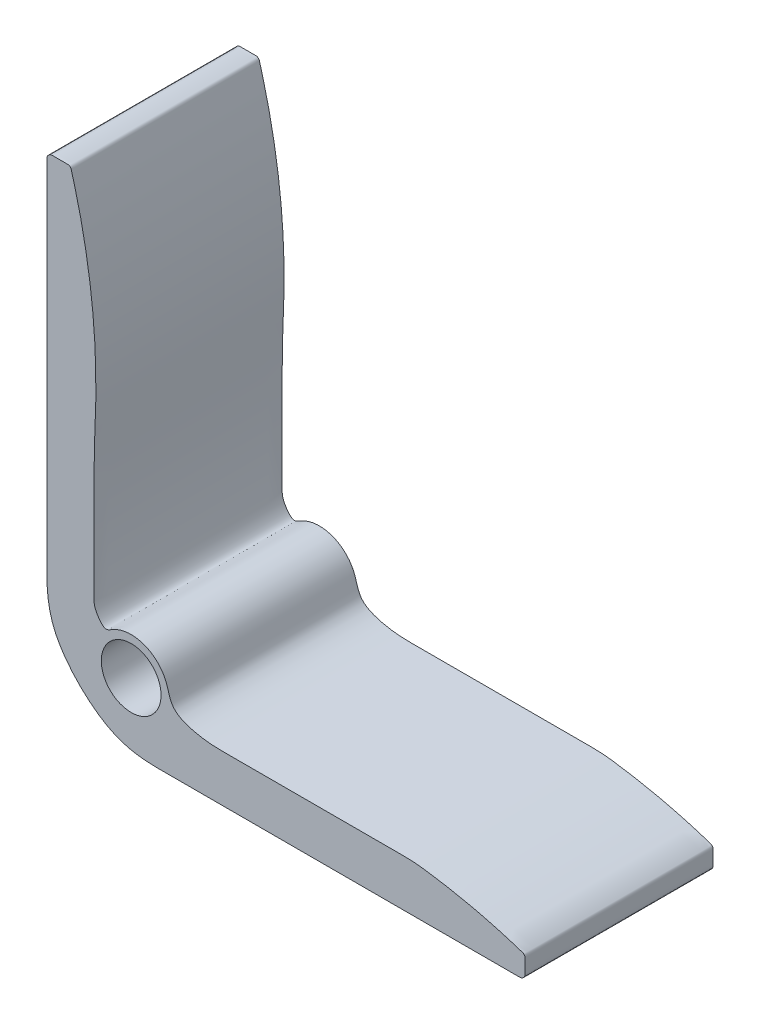
SolidWorks part; units mm, degrees
ref_plane "Alzado" through (0, 0, 0) normal (0, 0, 1) x (1, 0, 0)
ref_plane "Planta" through (0, 0, 0) normal (0, 1, 0) x (1, 0, 0)
ref_plane "Vista lateral" through (0, 0, 0) normal (1, 0, 0) x (0, 0, -1)
sketch "Croquis1" plane through (0, 0, 0) normal (0, 0, 1) x (1, 0, 0)
  line L0 (13.9712, -20.847) -> (-12.4747, -20.847) construction
  line L1 (25.847, -25.847) -> (-24.953, -25.847) construction
  line L2 (-19.953, -20.847) -> (-19.953, 19.953) construction
  line L3 (20.847, -20.847) -> (-19.953, -20.847) construction
  line L4 (-24.953, -25.847) -> (-24.953, 24.953) construction
  line L5 (25.847, -25.847) -> (0.447, -0.447) construction
  line L6 (-19.953, 19.953) -> (-24.953, 24.953) construction
  line L7 (-19.953, -18.3533) -> (-19.953, 0.7998) construction
  line L10 (25.847, 24.953) -> (-24.953, 24.953) construction
  line L11 (20.847, 19.953) -> (-19.953, 19.953) construction
  line L12 (0.447, -0.447) -> (-14.3951, -15.2892) construction
  line L13 (20.847, -20.847) -> (20.847, 19.953) construction
  line L14 (25.847, -25.847) -> (25.847, 24.953) construction
  line L15 (-21.6887, -22.5828) -> (-24.953, -25.847) construction
  line L16 (25.847, -25.847) -> (25.847, -23.4989) construction
  line L17 (-24.953, 24.953) -> (-22.453, 24.953) construction
  circle A0 centre (-15.9983, -18.9538) radius 3.175
  arc A1 (-12.4747, -20.847) -> (-19.953, -18.3533) centre (-15.9983, -18.9538) ccw construction
  arc A2 (25.847, -23.4989) -> (13.9712, -20.847) centre (7.3597, -78.3728) ccw construction
  arc A3 (-22.453, 24.953) -> (-19.953, 0.7998) centre (-87.0911, 6.0566) cw construction
  spline S0 degree 3 poles (-24.953, -13.147) (-24.953, -0.6554) (-24.953, 11.8363) (-24.953, 24.328) (-24.953, 24.4262) (-24.953, 24.6226) (-24.6226, 24.953) (-24.4262, 24.953) (-24.328, 24.953) (-23.9113, 24.953) (-23.4946, 24.953) (-23.078, 24.953) (-23.0431, 24.953) (-22.9735, 24.953) (-22.8691, 24.953) (-22.7994, 24.953) (-22.7646, 24.953) (-22.7091, 24.953) (-22.5982, 24.953) (-22.4119, 24.8126) (-22.3813, 24.706) (-22.3659, 24.6527) (-22.3563, 24.6193) (-22.3372, 24.5526) (-22.3087, 24.4523) (-22.2898, 24.3855) (-22.2803, 24.3521) (-20.674, 18.6619) (-19.8266, 12.8104) (-19.7527, 6.8984) (-19.7376, 5.6886) (-19.7726, 3.2683) (-19.953, -0.3589) (-19.953, -2.7786) (-19.953, -3.9885) (-19.953, -7.1807) (-19.953, -10.3729) (-19.953, -13.5651) (-19.953, -13.8672) (-19.953, -14.4714) (-18.8234, -16.0734) (-18.3437, -15.6996) (-18.086, -15.5419) (-15.8047, -14.146) (-13.2675, -14.992) (-12.2806, -17.4778) (-11.9834, -18.2263) (-11.8411, -19.9028) (-8.2792, -20.847) (-6.6686, -20.847) (-5.8632, -20.847) (-0.2675, -20.847) (5.3282, -20.847) (10.9239, -20.847) (11.1248, -20.847) (11.5266, -20.847) (12.1293, -20.847) (12.5311, -20.847) (12.732, -20.847) (13.0384, -20.847) (13.6511, -20.847) (14.5726, -20.912) (15.1793, -20.998) (15.4826, -21.0409) (15.6503, -21.0647) (15.9855, -21.1122) (16.4873, -21.1915) (16.8215, -21.2464) (16.9884, -21.2745) (19.8033, -21.7492) (22.5754, -22.4304) (25.2897, -23.3143) (25.3207, -23.3244) (25.3827, -23.3446) (25.4757, -23.3751) (25.5377, -23.3956) (25.5686, -23.4059) (25.6188, -23.4225) (25.7191, -23.4557) (25.847, -23.6329) (25.847, -23.7386) (25.847, -23.7914) (25.847, -23.8241) (25.847, -23.8896) (25.847, -23.9878) (25.847, -24.0532) (25.847, -24.0859) (25.847, -24.4773) (25.847, -24.8687) (25.847, -25.26) (25.847, -25.3523) (25.847, -25.5367) (25.5367, -25.847) (25.3523, -25.847) (25.26, -25.847) (12.7557, -25.847) (0.2514, -25.847) (-12.253, -25.847) (-14.2486, -25.847) (-18.2398, -25.847) (-24.953, -19.1339) (-24.953, -15.1427) (-24.953, -13.147) (-24.953, -0.6554) (-24.953, 11.8363) knots -0.032381 0 0 0 0.20269 0.20269 0.20269 0.204284 0.205878 0.207471 0.207471 0.207471 0.214232 0.214232 0.214232 0.214797 0.215362 0.215927 0.215927 0.215927 0.216827 0.217726 0.218626 0.218626 0.218626 0.21919 0.219753 0.220317 0.220317 0.220317 0.315703 0.315703 0.315703 0.335334 0.354965 0.374597 0.374597 0.374597 0.426393 0.426393 0.426393 0.431295 0.436198 0.4411 0.4411 0.4411 0.474199 0.474199 0.474199 0.487267 0.500334 0.513402 0.513402 0.513402 0.604198 0.604198 0.604198 0.607458 0.610718 0.613978 0.613978 0.613978 0.618949 0.62392 0.628892 0.628892 0.628892 0.631639 0.634386 0.637134 0.637134 0.637134 0.683368 0.683368 0.683368 0.683898 0.684427 0.684956 0.684956 0.684956 0.685813 0.686671 0.687528 0.687528 0.687528 0.688059 0.68859 0.689121 0.689121 0.689121 0.695471 0.695471 0.695471 0.696968 0.698465 0.699961 0.699961 0.699961 0.902857 0.902857 0.902857 0.935238 0.967619 1 1 1 1.20269 1.20269 1.20269 weights 1 1 1 1 1 1 1 1 1 1 1 1 1 1 1 1 1 1 1 1 1 1 1 1 1 1 1 0.99426 0.99426 1 1 1 1 1 1 1 1 1 1 1 1 1 1 0.762717 0.762717 1 1 1 1 1 1 1 1 1 1 1 1 1 1 1 1 1 1 1 1 1 1 1 1 0.998181 0.998181 1 1 1 1 1 1 1 1 1 1 1 1 1 1 1 1 1 1 1 1 1 1 1 1 1 1 1 1 1 1 1 1 1 1 only from (-24.953, -13.147) to (-24.953, -13.147)
  point P0 (0, 0)
  dimension "D3" = 6.35
  dimension "D5" = 8
  dimension "D1" = 50.8
  dimension "D2" = 50.8
  dimension "D4" = 5
extrude "Saliente-Extruir1" add sketch "Croquis1" along normal blind 20
